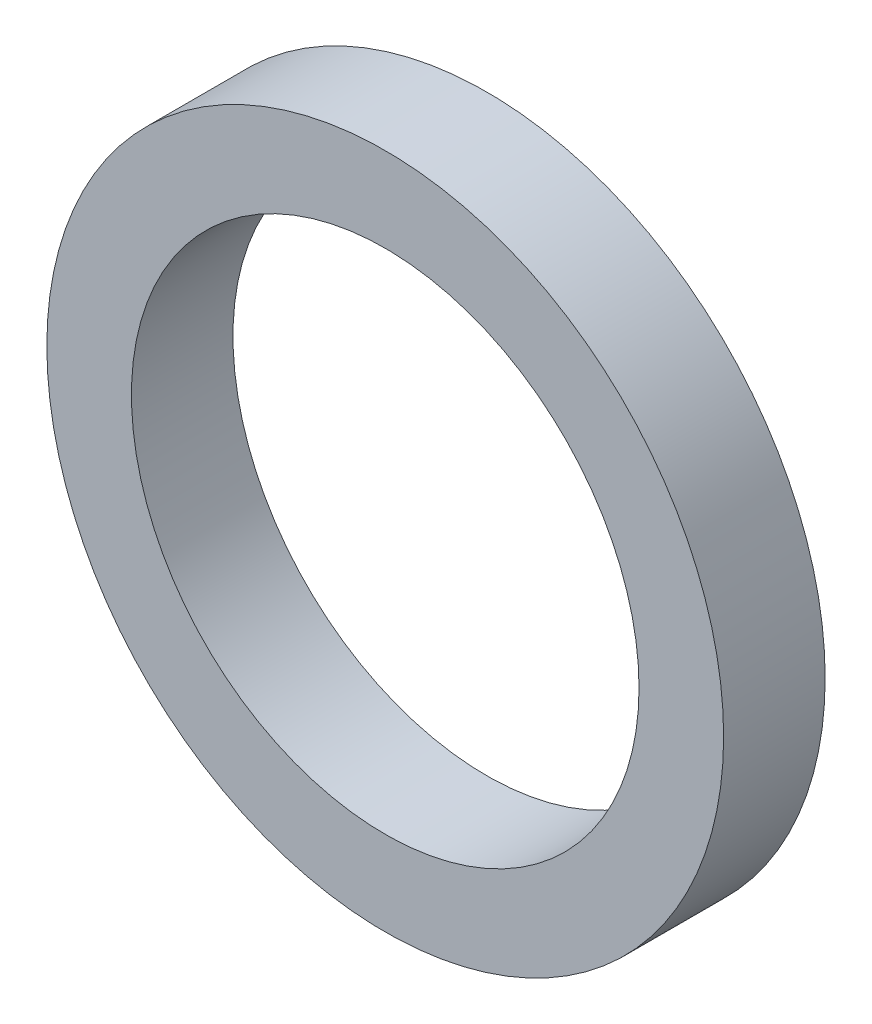
SolidWorks part; units mm, degrees
ref_plane "前视基准面" through (0, 0, 0) normal (0, 0, 1) x (1, 0, 0)
ref_plane "上视基准面" through (0, 0, 0) normal (0, 1, 0) x (1, 0, 0)
ref_plane "右视基准面" through (0, 0, 0) normal (1, 0, 0) x (0, 0, -1)
other "Configuration Table"
sketch "草图1" plane through (0, 0, 0) normal (0, 0, 1) x (1, 0, 0)
  circle A0 centre (0, 0) radius 20
  circle A1 centre (0, 0) radius 15
extrude "凸台-拉伸1" add sketch "草图1" along normal blind 6
